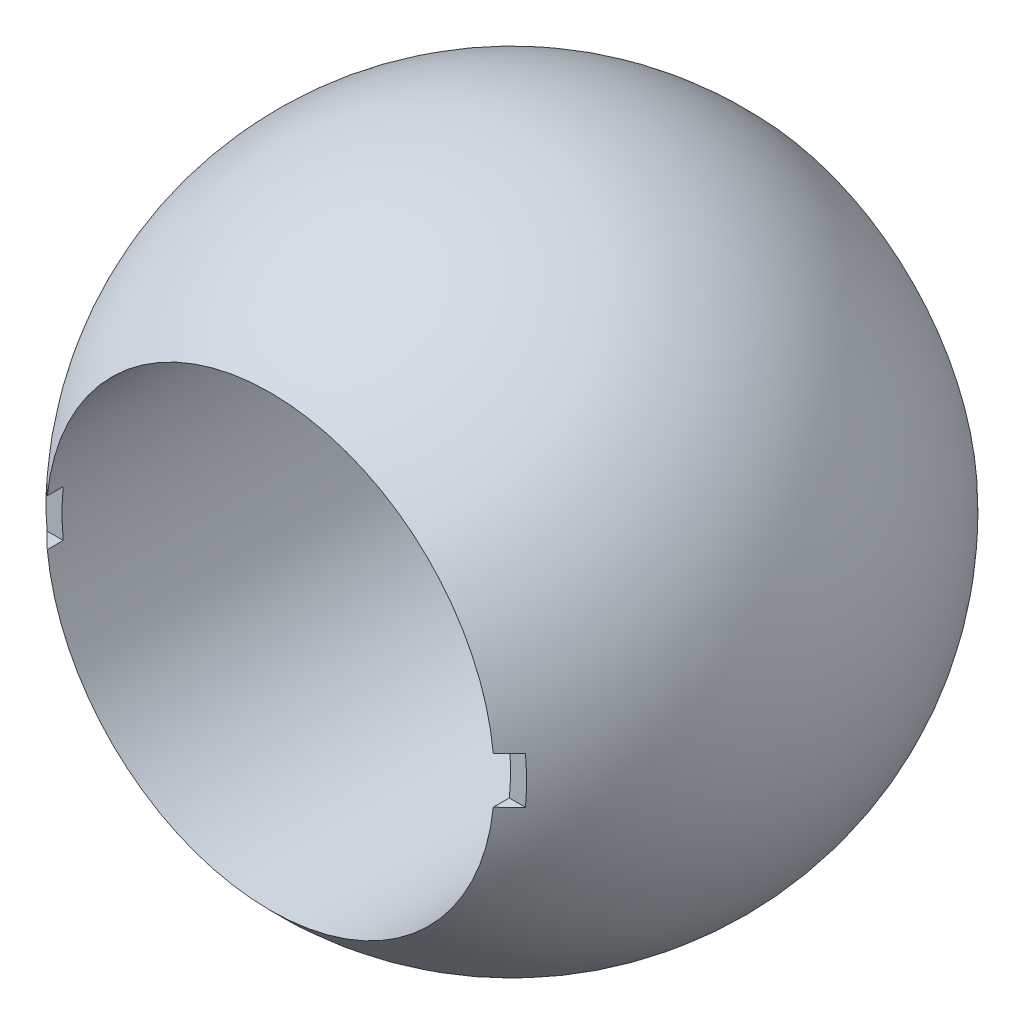
SolidWorks part; units mm, degrees
ref_plane "Front Plane" through (0, 0, 0) normal (0, 0, 1) x (1, 0, 0)
ref_plane "Top Plane" through (0, 0, 0) normal (0, 1, 0) x (1, 0, 0)
ref_plane "Right Plane" through (0, 0, 0) normal (1, 0, 0) x (0, 0, -1)
sketch "Sketch1" plane through (0, 0, 0) normal (0, 1, 0) x (1, 0, 0)
  line L0 (0, -55) -> (0, 55) construction
  line L1 (0, 7) -> (0, -7)
  arc A0 (0, 7) -> (0, -7) centre (0, 0) ccw
  dimension "D1" = 14
revolve "Revolve1" add sketch "Sketch1" angle 360 about L1
sketch "Sketch2" plane through (0, 0, 0) normal (0, 0, 1) x (1, 0, 0)
  circle A0 centre (0, 0) radius 4.7625
extrude "Cut-Extrude1" cut sketch "Sketch2" against normal through all and the other way through all
sketch "Sketch3" plane through (0, 0, 0) normal (1, 0, 0) x (0, 0, -1)
  line L0 (-5.1302, -4.7625) -> (-5.1302, 4.7625) construction
  line L1 (-5.4693, -0.4953) -> (-4.7911, -0.4953)
  line L2 (-5.4693, -0.4953) -> (-5.4693, 0.4953)
  line L3 (-5.4693, 0.4953) -> (-4.7911, 0.4953)
  line L4 (-4.7911, -0.4953) -> (-4.7911, 0.4953)
  line L5 (-5.4693, -0.4953) -> (-4.7911, 0.4953) construction
  line L6 (-5.4693, 0.4953) -> (-4.7911, -0.4953) construction
  point P0 (-5.1302, 0)
extrude "Cut-Extrude2" cut sketch "Sketch3" against normal through all and the other way through all
